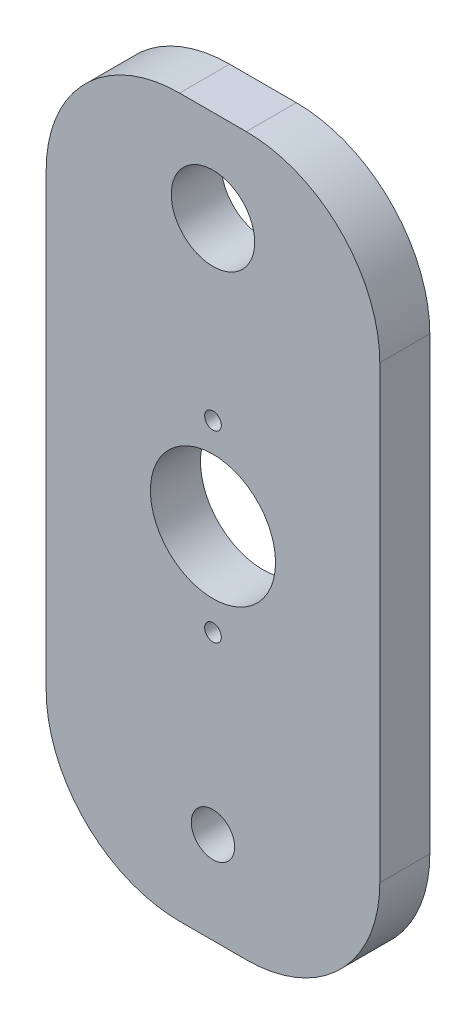
SolidWorks part; units mm, degrees
material "7075-T6 (SN)"
ref_plane "Piano frontale" through (0, 0, 0) normal (0, 0, 1) x (1, 0, 0)
ref_plane "Piano superiore" through (0, 0, 0) normal (0, 1, 0) x (1, 0, 0)
ref_plane "Piano destro" through (0, 0, 0) normal (1, 0, 0) x (0, 0, -1)
sketch "Schizzo2" plane through (0, 0, 0) normal (0, 0, 1) x (1, 0, 0)
  line L0 (0, 122.5423) -> (0, -121.3107) construction
  line L1 (20, 215) -> (-20, 215)
  line L2 (100, 135) -> (100, -135)
  line L3 (20, -215) -> (-20, -215)
  line L4 (-100, 135) -> (-100, -135)
  line L5 (100, 215) -> (-100, -215) construction
  line L6 (100, -215) -> (-100, 215) construction
  circle A0 centre (0, 0) radius 37.5
  circle A1 centre (0, -160) radius 13
  circle A2 centre (0, 160) radius 25
  arc A3 (20, 215) -> (100, 135) centre (20, 135) cw
  arc A4 (100, -135) -> (20, -215) centre (20, -135) cw
  arc A5 (-20, -215) -> (-100, -135) centre (-20, -135) cw
  arc A6 (-20, 215) -> (-100, 135) centre (-20, 135) ccw
  circle A7 centre (0, 55) radius 5
  circle A8 centre (0, -55) radius 5
  dimension "D1" = 75
  dimension "D2" = 26
  dimension "D3" = 50
  dimension "D8" = 80
  dimension "D9" = 10
  dimension "D4" = 160
  dimension "D5" = 160
  dimension "D6" = 430
  dimension "D7" = 200
  dimension "D10" = 55
  dimension "D11" = 55
extrude "Piastra" add sketch "Schizzo2" along normal blind 30
